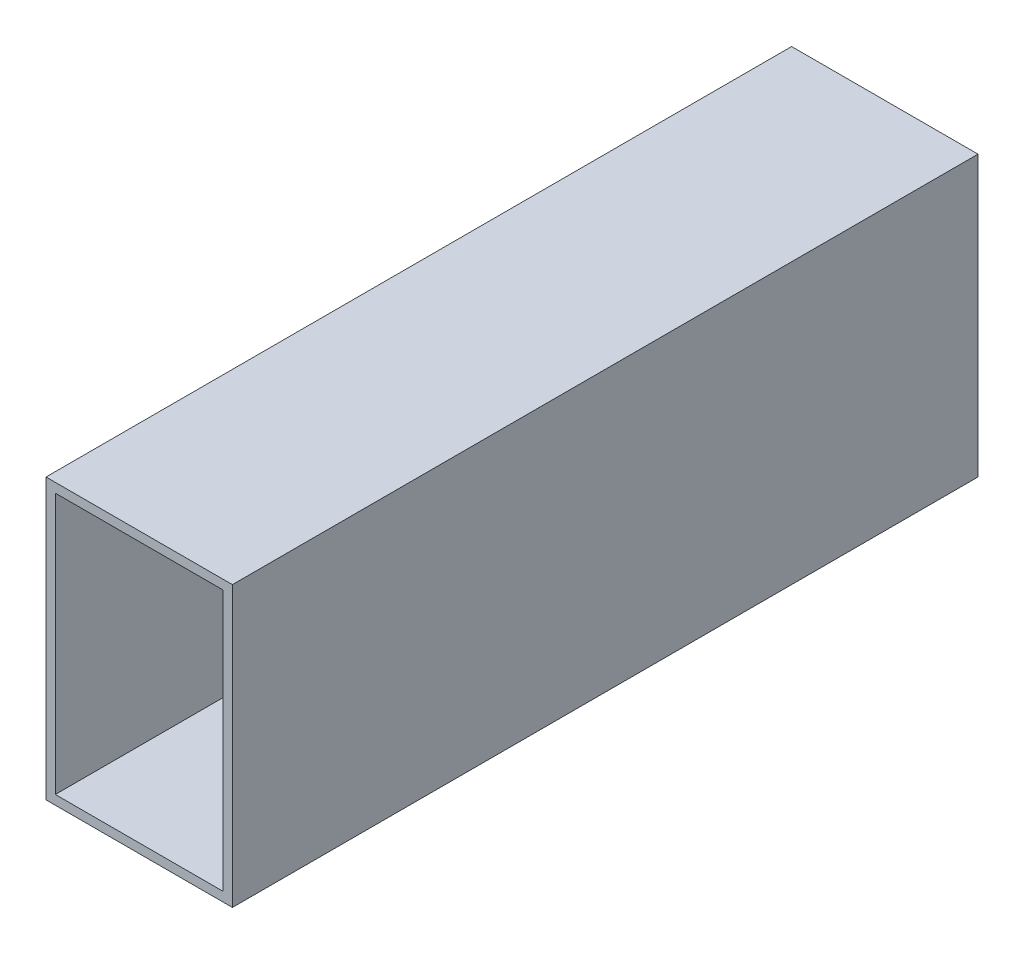
SolidWorks part; units mm, degrees
material "1060 Alloy"
ref_plane "Front Plane" through (0, 0, 0) normal (0, 0, 1) x (1, 0, 0)
ref_plane "Top Plane" through (0, 0, 0) normal (0, 1, 0) x (1, 0, 0)
ref_plane "Right Plane" through (0, 0, 0) normal (1, 0, 0) x (0, 0, -1)
sketch "Sketch1" plane through (0, 0, 0) normal (1, 0, 0) x (0, 0, -1)
  line L0 (0, 60) -> (0, 0) construction
  line L1 (-160, 60) -> (160, 60)
  line L2 (-160, 60) -> (-160, -60)
  line L3 (-160, -60) -> (160, -60)
  line L4 (160, 60) -> (160, -60)
  line L5 (0, 0) -> (0, -60) construction
  dimension "D1" = 320
  dimension "D2" = 120
extrude "Boss-Extrude1" add sketch "Sketch1" along normal mid plane 80
shell "Shell1" thickness 4
